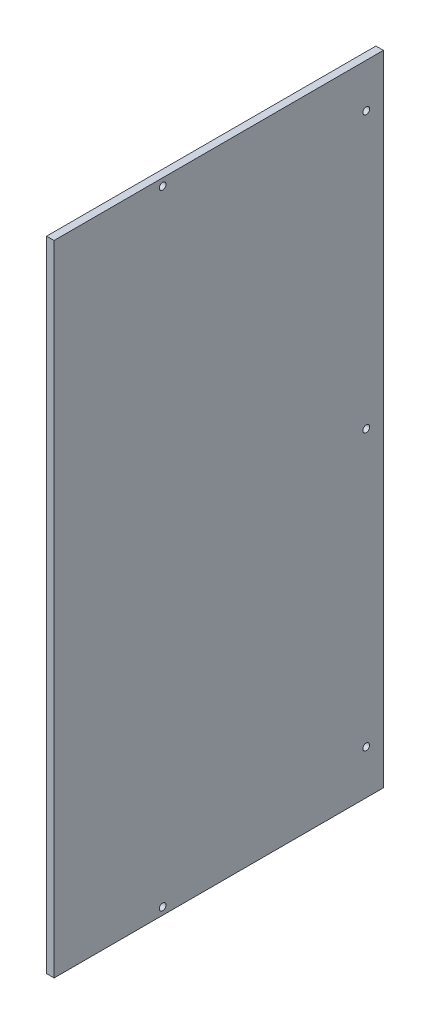
SolidWorks part; units mm, degrees
material "Acrylic (Medium-high impact)"
ref_plane "Front Plane" through (0, 0, 0) normal (0, 0, 1) x (1, 0, 0)
ref_plane "Top Plane" through (0, 0, 0) normal (0, 1, 0) x (1, 0, 0)
ref_plane "Right Plane" through (0, 0, 0) normal (1, 0, 0) x (0, 0, -1)
sketch "Sketch1" plane through (0, 0, 0) normal (1, 0, 0) x (0, 0, -1)
  line L1 (-66.5087, 289.7028) -> (143.0413, 289.7028)
  line L2 (-66.5087, 289.7028) -> (-66.5087, -116.6972)
  line L3 (-66.5087, -116.6972) -> (143.0413, -116.6972)
  line L4 (143.0413, 289.7028) -> (143.0413, -116.6972)
  dimension "D1" = 406.4
  dimension "D2" = 209.55
extrude "Boss-Extrude1" add sketch "Sketch1" along normal blind 4.7625
hole_wizard "#8 Clearance Hole1" positions "Sketch2" profile "Sketch3" hole size "#8" standard "ANSI Inch" end condition through all
sketch "Sketch2" plane through (0, 0, 0) normal (-1, 0, 0) x (0, 0, 1)
  point P0 (-132.1193, -88.6302)
  point P2 (-132.1193, 261.8898)
  point P5 (-132.1193, 86.6298)
  point P8 (-2.5793, -112.0617)
  point P10 (-2.5793, 285.0673)
sketch "Sketch3" plane through (0, -88.6302, -132.1193) normal (0, 1, 0) x (0, 0, 1)
  line L0 (0, 0) -> (0, 4.7625)
  line L1 (0, 4.7625) -> (2.1526, 4.7625)
  line L2 (2.1526, 4.7625) -> (2.1526, 0)
  line L5 (2.1526, 0) -> (0, 0)
  line L11 (0, -6.35) -> (0, 107.95) construction
  dimension "Thru Hole Dia." = 4.3053
  dimension "Thru Hole Depth" = 4.7625
